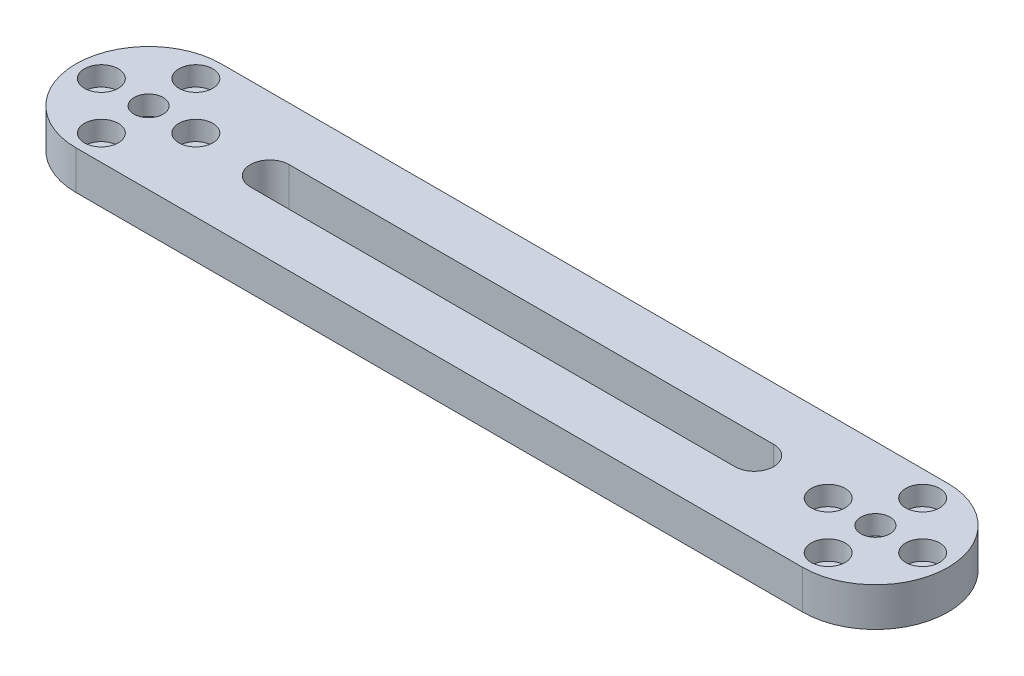
SolidWorks part; units mm, degrees
ref_plane "前视基准面" through (0, 0, 0) normal (0, 0, 1) x (1, 0, 0)
ref_plane "上视基准面" through (0, 0, 0) normal (0, 1, 0) x (1, 0, 0)
ref_plane "右视基准面" through (0, 0, 0) normal (1, 0, 0) x (0, 0, -1)
other "Configuration Table"
sketch "草图1" plane through (0, 0, 0) normal (0, 1, 0) x (1, 0, 0)
  line L0 (0, 0) -> (150, 0) construction
  line L1 (0, 15) -> (150, 15)
  line L2 (0, -15) -> (150, -15)
  line L3 (75, 0) -> (75, -50000) construction
  line L4 (0, 0) -> (50000, 0) construction
  arc A0 (0, 15) -> (0, -15) centre (0, 0) ccw
  arc A1 (150, -15) -> (150, 15) centre (150, 0) ccw
  circle A2 centre (0, 0) radius 9.75 construction
  circle A3 centre (150, 0) radius 9.75 construction
  circle A4 centre (0, 0) radius 1.6
  circle A5 centre (150, 0) radius 1.6
  circle A6 centre (9.7105, 0) radius 1.6
  circle A7 centre (-9.75, 0) radius 1.6
  circle A8 centre (0, -9.75) radius 2.1
  circle A9 centre (0, 9.75) radius 2.1
  circle A10 centre (150, 9.75) radius 2.1
  circle A11 centre (159.75, 0) radius 1.6
  circle A12 centre (150, -9.75) radius 2.1
  circle A13 centre (150, 0) radius 1.6
  circle A14 centre (140.2895, 0) radius 1.6
  point P3 (75, 0)
  dimension "D3" = 19.5
  dimension "D4" = 19.5
  dimension "D5" = 3.2
  dimension "D6" = 3.2
  dimension "D7" = 3.2
  dimension "D8" = 3.2
  dimension "D9" = 4.2
  dimension "D10" = 4.2
  dimension "D1" = 30
  dimension "D2" = 150
extrude "凸台-拉伸2" add sketch "草图1" along normal blind 8 contours L2 A1 L1 A0 A12 A10 A9 A8 A7 A6 A5 A4 A11 A14
sketch "草图3" plane through (0, 8, 0) normal (0, 1, 0) x (1, 0, 0)
  line L0 (75, -17) -> (75, -50017) construction
  line L1 (0, -15) -> (150, -15) construction
  circle A2 centre (0, 0) radius 9.75 construction
  circle A3 centre (0, 0) radius 3
  circle A4 centre (0, 9.75) radius 3.5
  circle A5 centre (9.75, 0) radius 3.5
  circle A6 centre (0, -9.75) radius 3.5
  circle A7 centre (-9.75, 0) radius 3.5
  circle A8 centre (150, 0) radius 9.75 construction
  circle A9 centre (159.75, 0) radius 3.5
  circle A10 centre (150, -9.75) radius 3.5
  circle A11 centre (140.25, 0) radius 3.5
  circle A12 centre (150, 9.75) radius 3.5
  circle A13 centre (150, 0) radius 3
  point P2 (150, -9.75)
  point P18 (0, 0)
  point P20 (75, -15)
  point P32 (150, 0)
  dimension "D1" = 6
  dimension "D2" = 7
  dimension "D4" = 19.5
  dimension "D3" = 4
extrude "切除-拉伸2" cut sketch "草图3" against normal blind 4
sketch "草图4" plane through (0, 8, 0) normal (0, 1, 0) x (1, 0, 0)
  line L0 (75, -17) -> (75, 49983) construction
  line L1 (0, -15) -> (150, -15) construction
  line L2 (0, 0) -> (50000, 0) construction
  line L3 (25, 0) -> (125, 0) construction
  line L4 (25, 4) -> (125, 4)
  line L5 (25, -4) -> (125, -4)
  line L6 (0, 15) -> (150, 15) construction
  arc A0 (25, 4) -> (25, -4) centre (25, 0) ccw
  arc A1 (125, -4) -> (125, 4) centre (125, 0) ccw
  point P4 (75, -15)
  point P10 (75, 0)
  dimension "D1" = 100
  dimension "D2" = 11
extrude "切除-拉伸3" cut sketch "草图4" against normal blind 14
